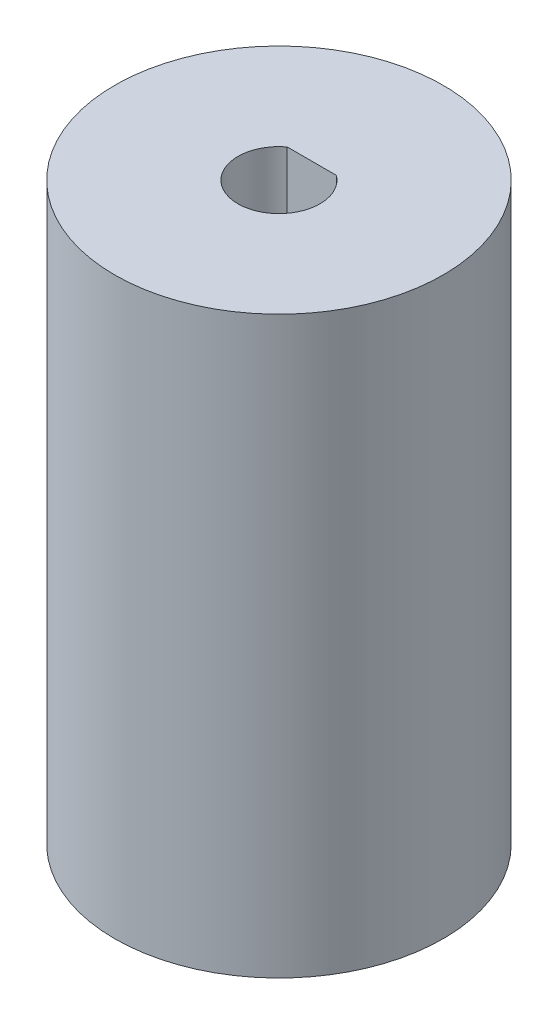
SolidWorks part; units mm, degrees
ref_plane "Front Plane" through (0, 0, 0) normal (0, 0, 1) x (1, 0, 0)
ref_plane "Top Plane" through (0, 0, 0) normal (0, 1, 0) x (1, 0, 0)
ref_plane "Right Plane" through (0, 0, 0) normal (1, 0, 0) x (0, 0, -1)
sketch "Sketch1" plane through (0, 0, 0) normal (0, 1, 0) x (1, 0, 0)
  circle A0 centre (0, 0) radius 10
  dimension "D1" = 20
extrude "Boss-Extrude1" add sketch "Sketch1" along normal blind 35
sketch "Sketch3" plane through (0, 0, 0) normal (0, -1, 0) x (1, 0, 0)
  circle A0 centre (0, 0) radius 4
  dimension "D1" = 8
extrude "Cut-Extrude2" cut sketch "Sketch3" against normal blind 15
sketch "Sketch2" plane through (0, 35, 0) normal (0, 1, 0) x (1, 0, 0)
  line L0 (-1.5, 2) -> (1.5, 2)
  circle A0 centre (0, 0) radius 2.5
  dimension "D1" = 5
  dimension "D2" = 2
extrude "Cut-Extrude1" cut sketch "Sketch2" against normal blind 15 contours L0 A0
